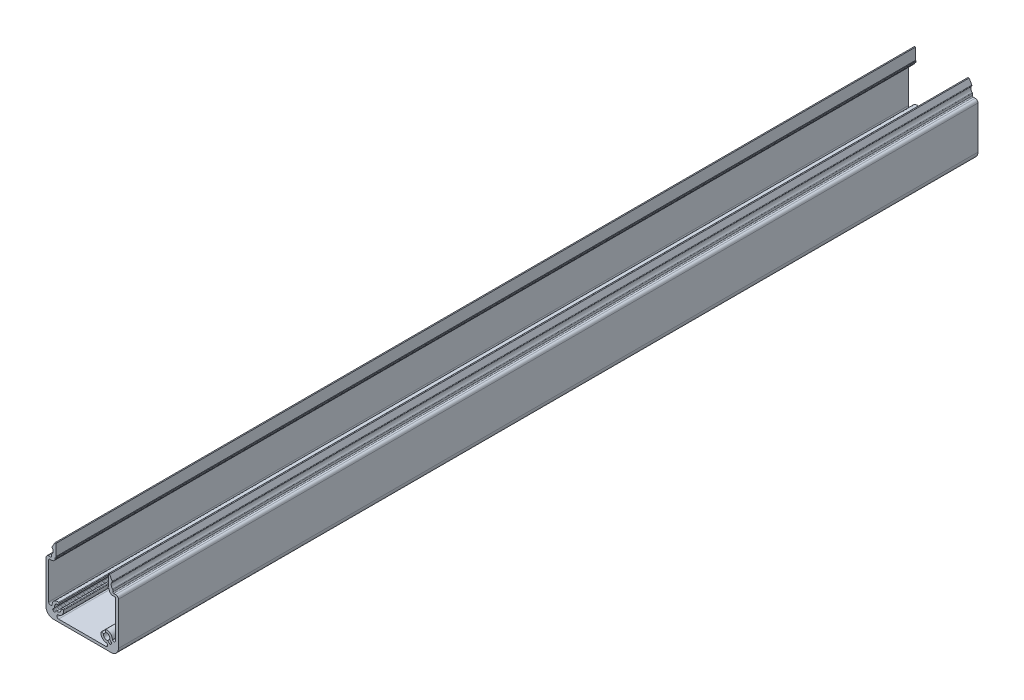
SolidWorks part; units mm, degrees
ref_plane "Front Plane" through (0, 0, 0) normal (0, 0, 1) x (1, 0, 0)
ref_plane "Top Plane" through (0, 0, 0) normal (0, 1, 0) x (1, 0, 0)
ref_plane "Right Plane" through (0, 0, 0) normal (1, 0, 0) x (0, 0, -1)
ref_plane "Plane1" through (0, 0, 20) normal (0, 0, 1) x (1, 0, 0)
sketch "Sketch1" plane through (0, 0, 20) normal (0, 0, 1) x (1, 0, 0)
  line L0 (4, 0) -> (36, 0)
  line L1 (40, 4) -> (40, 27.5)
  line L2 (38.5, 29) -> (37.4085, 29)
  line L3 (36.9085, 29.5) -> (36.9085, 30.572)
  line L4 (36.583, 34.4315) -> (35.1, 37)
  line L5 (35.1, 37) -> (34.5, 37)
  line L6 (34.5, 37) -> (34.5, 30.6727)
  line L7 (34.5, 30.6727) -> (34.1585, 30.5611)
  line L8 (34.1585, 30.5611) -> (34.1585, 29.9899)
  line L9 (34.1585, 29.9899) -> (34.9085, 29.9899)
  line L10 (34.9085, 29.9899) -> (34.9085, 29.7)
  line L11 (36.9085, 27.7) -> (38, 27.7)
  line L12 (38.5, 27.2) -> (38.5, 6.9548)
  line L13 (36.7929, 6.2477) -> (36.6482, 6.3924)
  line L14 (32.7665, 9.2376) -> (33.0471, 8.1904)
  line L15 (35.1484, 5.9123) -> (36.1464, 4.9142)
  line L16 (36.1464, 4.2071) -> (35.7929, 3.8536)
  line L17 (35.0858, 3.8536) -> (34.0877, 4.8516)
  line L18 (31.8096, 6.9529) -> (30.7624, 7.2335)
  line L19 (33.6076, 3.3518) -> (33.7523, 3.2071)
  line L20 (33.0452, 1.5) -> (6.9548, 1.5)
  line L21 (6.2477, 3.2071) -> (6.3924, 3.3518)
  line L22 (9.2376, 7.2335) -> (8.1904, 6.9529)
  line L23 (5.9123, 4.8516) -> (4.9142, 3.8536)
  line L24 (4.2071, 3.8536) -> (3.8536, 4.2071)
  line L25 (3.8536, 4.9142) -> (4.8516, 5.9123)
  line L26 (6.9529, 8.1904) -> (7.2335, 9.2376)
  line L27 (3.3518, 6.3924) -> (3.2071, 6.2477)
  line L28 (1.5, 6.9548) -> (1.5, 27.2)
  line L29 (2, 27.7) -> (3.0915, 27.7)
  line L30 (5.0915, 29.7) -> (5.0915, 29.9899)
  line L31 (5.0915, 29.9899) -> (5.8415, 29.9899)
  line L32 (5.8415, 29.9899) -> (5.8415, 30.5611)
  line L33 (5.8415, 30.5611) -> (5.5, 30.6727)
  line L34 (5.5, 30.6727) -> (5.5, 37)
  line L35 (5.5, 37) -> (4.9, 37)
  line L36 (4.9, 37) -> (3.417, 34.4315)
  line L37 (3.0915, 30.572) -> (3.0915, 29.5)
  line L38 (2.5915, 29) -> (1.5, 29)
  line L39 (0, 27.5) -> (0, 4)
  arc A0 (36, 0) -> (40, 4) centre (36, 4) ccw
  arc A1 (40, 27.5) -> (38.5, 29) centre (38.5, 27.5) ccw
  arc A2 (37.4085, 29) -> (36.9085, 29.5) centre (37.4085, 29.5) cw
  arc A3 (36.9085, 30.572) -> (36.7268, 30.9576) centre (36.4085, 30.572) ccw
  arc A4 (36.7268, 30.9576) -> (36.52, 33.8452) centre (38, 32.5) cw
  arc A5 (36.52, 33.8452) -> (36.583, 34.4315) centre (36.1499, 34.1815) ccw
  arc A6 (34.9085, 29.7) -> (36.9085, 27.7) centre (36.9085, 29.7) ccw
  arc A7 (38, 27.7) -> (38.5, 27.2) centre (38, 27.2) cw
  arc A8 (38.5, 6.9548) -> (36.7929, 6.2477) centre (37.5, 6.9548) cw
  arc A9 (36.6482, 6.3924) -> (33.0095, 9.6116) centre (33.5, 6.5) ccw
  arc A10 (33.0095, 9.6116) -> (32.7665, 9.2376) centre (33.0562, 9.3152) ccw
  arc A11 (33.0471, 8.1904) -> (35.1484, 5.9123) centre (33.5, 6.5) cw
  arc A12 (36.1464, 4.9142) -> (36.1464, 4.2071) centre (35.7929, 4.5607) cw
  arc A13 (35.7929, 3.8536) -> (35.0858, 3.8536) centre (35.4393, 4.2071) cw
  arc A14 (34.0877, 4.8516) -> (31.8096, 6.9529) centre (33.5, 6.5) cw
  arc A15 (30.7624, 7.2335) -> (30.3884, 6.9905) centre (30.6848, 6.9438) ccw
  arc A16 (30.3884, 6.9905) -> (33.6076, 3.3518) centre (33.5, 6.5) ccw
  arc A17 (33.7523, 3.2071) -> (33.0452, 1.5) centre (33.0452, 2.5) cw
  arc A18 (6.9548, 1.5) -> (6.2477, 3.2071) centre (6.9548, 2.5) cw
  arc A19 (6.3924, 3.3518) -> (9.6116, 6.9905) centre (6.5, 6.5) ccw
  arc A20 (9.6116, 6.9905) -> (9.2376, 7.2335) centre (9.3152, 6.9438) ccw
  arc A21 (8.1904, 6.9529) -> (5.9123, 4.8516) centre (6.5, 6.5) cw
  arc A22 (4.9142, 3.8536) -> (4.2071, 3.8536) centre (4.5607, 4.2071) cw
  arc A23 (3.8536, 4.2071) -> (3.8536, 4.9142) centre (4.2071, 4.5607) cw
  arc A24 (4.8516, 5.9123) -> (6.9529, 8.1904) centre (6.5, 6.5) cw
  arc A25 (7.2335, 9.2376) -> (6.9905, 9.6116) centre (6.9438, 9.3152) ccw
  arc A26 (6.9905, 9.6116) -> (3.3518, 6.3924) centre (6.5, 6.5) ccw
  arc A27 (3.2071, 6.2477) -> (1.5, 6.9548) centre (2.5, 6.9548) cw
  arc A28 (1.5, 27.2) -> (2, 27.7) centre (2, 27.2) cw
  arc A29 (3.0915, 27.7) -> (5.0915, 29.7) centre (3.0915, 29.7) ccw
  arc A30 (3.417, 34.4315) -> (3.48, 33.8452) centre (3.8501, 34.1815) ccw
  arc A31 (3.48, 33.8452) -> (3.2732, 30.9576) centre (2, 32.5) cw
  arc A32 (3.2732, 30.9576) -> (3.0915, 30.572) centre (3.5915, 30.572) ccw
  arc A33 (3.0915, 29.5) -> (2.5915, 29) centre (2.5915, 29.5) cw
  arc A34 (1.5, 29) -> (0, 27.5) centre (1.5, 27.5) ccw
  arc A35 (0, 4) -> (4, 0) centre (4, 4) ccw
extrude "Boss-Extrude1" add sketch "Sketch1" against normal blind 475
